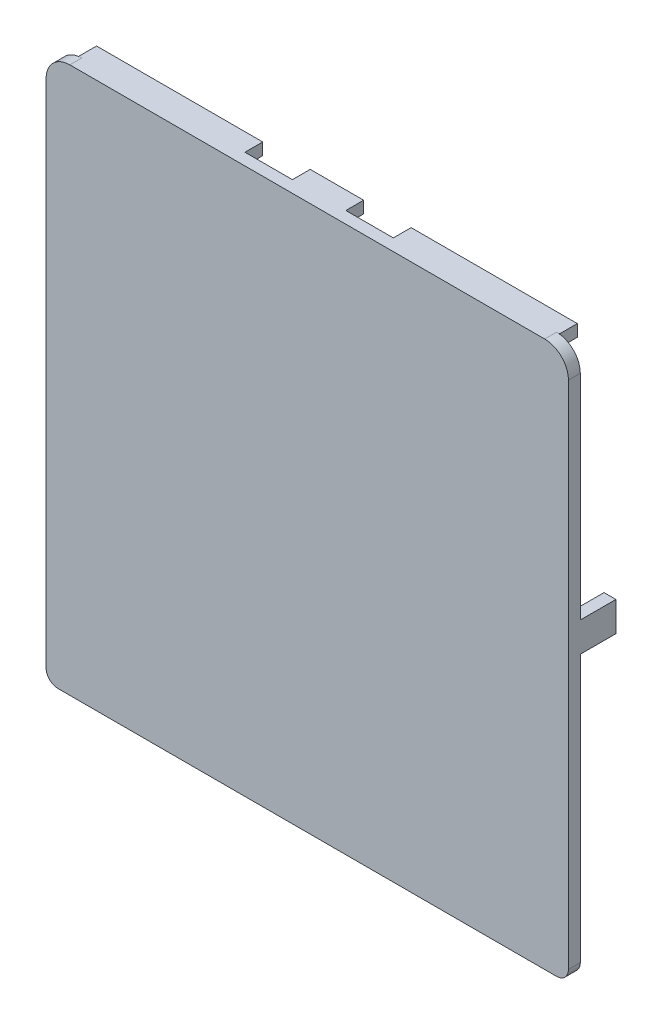
SolidWorks part; units mm, degrees
ref_plane "Front Plane" through (0, 0, 0) normal (0, 0, 1) x (1, 0, 0)
ref_plane "Top Plane" through (0, 0, 0) normal (0, 1, 0) x (1, 0, 0)
ref_plane "Right Plane" through (0, 0, 0) normal (1, 0, 0) x (0, 0, -1)
sketch "Sketch1" plane through (0, 0, 0) normal (0, 0, 1) x (1, 0, 0)
  line L1 (-73.8547, 63.883) -> (14.1453, 63.883)
  line L2 (-73.8547, 63.883) -> (-73.8547, -28.117)
  line L3 (-73.8547, -28.117) -> (14.1453, -28.117)
  line L4 (14.1453, 63.883) -> (14.1453, -28.117)
  dimension "D1" = 88
  dimension "D2" = 92
extrude "Boss-Extrude1" add sketch "Sketch1" along normal blind 2
fillet "Fillet1" radius 4 2 edges at (-73.8547, 63.883, 1) (14.1453, 63.883, 1)
sketch "Sketch3" plane through (0, 0, 0) normal (0, 0, -1) x (-1, 0, 0)
  line L0 (-10.1453, 63.883) -> (69.8547, 63.883) construction
  line L1 (70.3547, 63.883) -> (42.3547, 63.883)
  line L2 (70.3547, 63.883) -> (70.3547, 61.883)
  line L3 (70.3547, 61.883) -> (42.3547, 61.883)
  line L4 (42.3547, 63.883) -> (42.3547, 61.883)
  line L5 (73.8547, 59.883) -> (73.8547, -28.117) construction
  line L6 (34.3547, 63.883) -> (25.3547, 63.883)
  line L7 (34.3547, 63.883) -> (34.3547, 61.883)
  line L8 (34.3547, 61.883) -> (25.3547, 61.883)
  line L9 (25.3547, 63.883) -> (25.3547, 61.883)
  line L10 (17.3547, 63.883) -> (-10.6453, 63.883)
  line L11 (17.3547, 63.883) -> (17.3547, 61.883)
  line L12 (17.3547, 61.883) -> (-10.6453, 61.883)
  line L13 (-10.6453, 63.883) -> (-10.6453, 61.883)
  line L14 (-14.1453, -28.117) -> (-14.1453, 59.883) construction
  dimension "D1" = 2
  dimension "D2" = 2
  dimension "D3" = 2
  dimension "D4" = 28
  dimension "D5" = 9
  dimension "D6" = 28
  dimension "D7" = 8
  dimension "D8" = 8
  dimension "D9" = 3.5
  dimension "D10" = 3.5
extrude "Boss-Extrude3" add sketch "Sketch3" along normal blind 3
sketch "Sketch4" plane through (0, 0, 0) normal (0, 0, -1) x (-1, 0, 0)
  line L0 (-14.1453, -28.117) -> (-14.1453, 59.883) construction
  line L1 (-12.1453, 18.883) -> (-14.1453, 18.883)
  line L2 (-12.1453, 18.883) -> (-12.1453, 23.883)
  line L3 (-12.1453, 23.883) -> (-14.1453, 23.883)
  line L4 (-14.1453, 18.883) -> (-14.1453, 23.883)
  line L5 (-12.1453, 23.883) -> (-14.1453, 23.883) construction
  point P7 (-13.1453, 23.883)
  dimension "D1" = 0
extrude "Boss-Extrude4" add sketch "Sketch4" along normal blind 6
fillet "Fillet2" radius 2 2 edges at (14.1453, -28.117, 1) (-73.8547, -28.117, 1)
sketch "Sketch5" plane through (0, 0, 0) normal (0, 0, -1) x (-1, 0, 0)
  line L0 (73.8547, 59.883) -> (73.8547, -26.117) construction
  line L1 (71.8547, -26.117) -> (68.8547, -26.117)
  line L2 (71.8547, -26.117) -> (71.8547, 54.7492)
  line L3 (71.8547, 54.7492) -> (68.8547, 54.7492)
  line L5 (68.8547, -26.117) -> (-12.1453, -26.117)
  line L7 (68.8547, -23.117) -> (-9.1453, -23.117)
  line L8 (-12.1453, -26.117) -> (-12.1453, -23.117)
  line L10 (-12.1453, -23.117) -> (-12.1453, 54.89)
  line L11 (-12.1453, 54.89) -> (-9.1453, 54.89)
  line L12 (-9.1453, -23.117) -> (-9.1453, 54.89)
  line L13 (71.8547, -28.117) -> (-12.1453, -28.117) construction
  line L14 (-14.1453, -26.117) -> (-14.1453, 18.883) construction
  line L16 (68.8547, -23.117) -> (68.8547, 54.7492)
  dimension "D1" = 3
  dimension "D2" = 3
  dimension "D3" = 3
  dimension "D4" = 2
  dimension "D5" = 2
  dimension "D6" = 2
extrude "Boss-Extrude5" add sketch "Sketch5" along normal blind 2
fillet "Fillet4" radius 0.5 4 edges at (-71.8547, 14.3161, -2) (-29.8547, -26.117, -2) (12.1453, -3.617, -2) (12.1453, 39.3865, -2)
